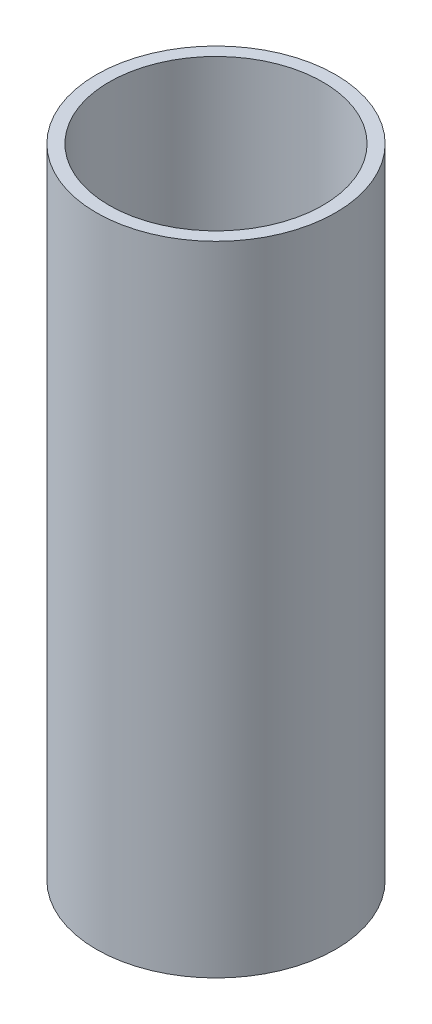
SolidWorks part; units mm, degrees
material "PP Homopolymer"
ref_plane "Front Plane" through (0, 0, 0) normal (0, 0, 1) x (1, 0, 0)
ref_plane "Top Plane" through (0, 0, 0) normal (0, 1, 0) x (1, 0, 0)
ref_plane "Right Plane" through (0, 0, 0) normal (1, 0, 0) x (0, 0, -1)
sketch "Sketch1" plane through (0, 0, 0) normal (0, 1, 0) x (1, 0, 0)
  circle A0 centre (0, 0) radius 37.5
  circle A1 centre (0, 0) radius 33.5
  dimension "D1" = 75
  dimension "D2" = 67
extrude "Boss-Extrude1" add sketch "Sketch1" along normal blind 200
